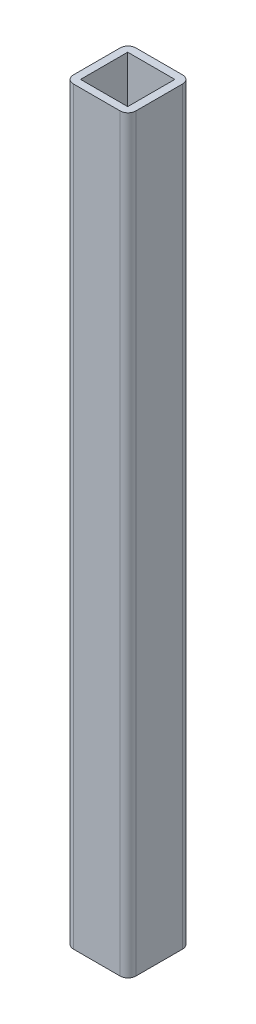
SolidWorks part; units mm, degrees
ref_plane "Front" through (0, 0, 0) normal (0, 0, 1) x (1, 0, 0)
ref_plane "Top" through (0, 0, 0) normal (0, 1, 0) x (1, 0, 0)
ref_plane "Right" through (0, 0, 0) normal (1, 0, 0) x (0, 0, -1)
sketch "Sketch1" plane through (0, 0, 0) normal (0, 1, 0) x (1, 0, 0)
  line L0 (25.4, 25.4) -> (-25.4, -25.4) construction
  line L1 (-19.05, -25.4) -> (19.05, -25.4)
  line L2 (-25.4, -19.05) -> (-25.4, 19.05)
  line L3 (-19.05, 25.4) -> (19.05, 25.4)
  line L4 (25.4, -19.05) -> (25.4, 19.05)
  line L5 (-19.304, 19.05) -> (19.05, 19.05)
  line L6 (19.05, -19.304) -> (19.05, 19.05)
  line L7 (-19.304, -19.304) -> (19.05, -19.304)
  line L8 (-19.304, -19.304) -> (-19.304, 19.05)
  arc A0 (-19.05, 25.4) -> (-25.4, 19.05) centre (-19.05, 19.05) ccw
  arc A1 (25.4, 19.05) -> (19.05, 25.4) centre (19.05, 19.05) ccw
  arc A2 (19.05, -25.4) -> (25.4, -19.05) centre (19.05, -19.05) ccw
  arc A3 (-25.4, -19.05) -> (-19.05, -25.4) centre (-19.05, -19.05) ccw
  point P5 (0, 0)
  point P8 (-25.4, 25.4)
extrude "Extrude1" add sketch "Sketch1" along normal blind 609.6
sketch "Sketch3" plane through (0, 0, 25.4) normal (0, 0, 1) x (1, 0, 0)
  line L0 (-25.4, 609.6) -> (-25.4, 0) construction
  line L1 (-19.05, 0) -> (19.05, 0) construction
  circle A0 centre (0, 177.8) radius 6.35
  dimension "D1" = 12.7
  dimension "D2" = 25.4
  dimension "D3" = 177.8
extrude "Cut-Extrude1" [suppressed] cut sketch "Sketch3" against normal through all
